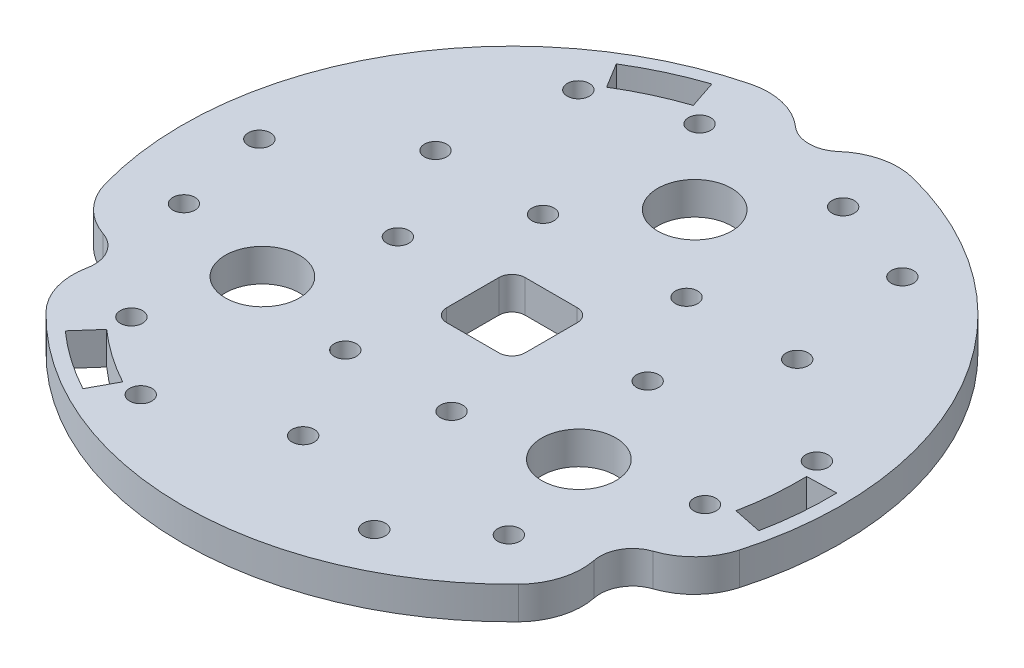
SolidWorks part; units mm, degrees
ref_plane "Front Plane" through (0, 0, 0) normal (0, 0, 1) x (1, 0, 0)
ref_plane "Top Plane" through (0, 0, 0) normal (0, 1, 0) x (1, 0, 0)
ref_plane "Right Plane" through (0, 0, 0) normal (1, 0, 0) x (0, 0, -1)
sketch "Sketch1" plane through (0, 0, 0) normal (0, 1, 0) x (1, 0, 0)
  line L0 (0, 0) -> (24.2487, -14) construction
  line L2 (0, 0) -> (0, 28) construction
  line L3 (0, 0) -> (-24.2487, -14) construction
  circle A0 centre (0, 0) radius 50.5
  circle A4 centre (0, 0) radius 28 construction
  circle A19 centre (0, 28) radius 5.675
  circle A20 centre (24.2487, -14) radius 5.675
  circle A21 centre (-24.2487, -14) radius 5.675
  point P13 (0, 0)
  point P38 (0, 0)
  dimension "D3" = 101
  dimension "D1" = 11.35
  dimension "D2" = 56
extrude "Boss-Extrude1" add sketch "Sketch1" along normal blind 5
sketch "Sketch4" plane through (0, 0, 0) normal (0, 1, 0) x (1, 0, 0)
  line L0 (0, 0) -> (27.7128, 16) construction
  line L1 (0, 0) -> (50.5, 0) construction
  line L2 (0, 0) -> (0, -32) construction
  line L3 (0, 0) -> (-27.7128, 16) construction
  circle A8 centre (27.7128, 16) radius 1.7
  circle A10 centre (0, 0) radius 50.5 construction
  circle A11 centre (0, -32) radius 1.7
  circle A12 centre (-27.7128, 16) radius 1.7
  point P12 (0, 0)
  dimension "D4" = 3.4
  dimension "D5" = 32
  dimension "D7" = 30
extrude "Cut-Extrude5" cut sketch "Sketch4" along normal through all
sketch "Sketch8" plane through (0, 5, 0) normal (0, 1, 0) x (1, 0, 0)
  line L0 (0, 0) -> (0, 28) construction
  line L3 (0, 28) -> (0, 50.5) construction
  circle A0 centre (0, 28) radius 5.675 construction
  circle A1 centre (0, 28) radius 5.675 construction
  circle A2 centre (11, 39.75) radius 1.7
  circle A4 centre (11, 15.75) radius 1.7
  circle A5 centre (-11, 39.75) radius 1.7
  circle A6 centre (-11, 15.75) radius 1.7
  circle A7 centre (0, 0) radius 50.5 construction
  dimension "D1" = 3.4
  dimension "D2" = 22
  dimension "D3" = 24
  dimension "D4" = 12.25
extrude "Cut-Extrude9" cut sketch "Sketch8" against normal through all
sketch "Sketch9" plane through (0, 0, 0) normal (0, -1, 0) x (1, 0, 0)
  line L0 (0, 0) -> (0, 45) construction
  line L1 (7.5, 45) -> (-7.5, 45) construction
  line L2 (-7.5, 45) -> (-17.8923, 39) construction
  line L3 (7.5, 45) -> (17.8923, 39) construction
  circle A0 centre (-17.8923, 39) radius 1.7
  circle A1 centre (17.8923, 39) radius 1.7
  dimension "D5" = 3.4
  dimension "D1" = 7.5
  dimension "D2" = 12
  dimension "D3" = 45
  dimension "D4" = 150
extrude "Cut-Extrude10" cut sketch "Sketch9" against normal through all
pattern_circular "CirPattern3" count 3 over 360 about axis through (0, 0, 0) along (0, 1, 0) of "Cut-Extrude9", "Cut-Extrude10"
sketch "Sketch10" plane through (0, 5, 0) normal (0, 1, 0) x (1, 0, 0)
  line L0 (0, 0) -> (-21.3422, 45.7685) construction
  line L1 (0, 0) -> (0, 50.5) construction
  line L2 (-13.9432, 41.7323) -> (-15.3692, 46.0004)
  line L3 (-23.0063, 37.5061) -> (-25.3592, 41.342)
  circle A0 centre (0, 0) radius 50.5 construction
  arc A2 (-25.3592, 41.342) -> (-15.3692, 46.0004) centre (0, 0) cw
  arc A3 (-23.0063, 37.5061) -> (-13.9432, 41.7323) centre (0, 0) cw
  point P5 (-18.5952, 39.8775)
  point P10 (-20.2671, 43.4629)
  point P13 (-18.7145, 40.1335)
  point P15 (-20.497, 43.9559)
  dimension "D2" = 2
  dimension "D3" = 4.5
  dimension "D5" = 10
  dimension "D1" = 25
  dimension "D4" = 4.5
extrude "Cut-Extrude11" cut sketch "Sketch10" against normal through all
pattern_circular "CirPattern4" count 3 over 360 about axis through (0, 0, 0) along (0, 1, 0) of "Cut-Extrude11"
sketch "Sketch11" plane through (0, 5, 0) normal (0, 1, 0) x (1, 0, 0)
  line L1 (-6, -6) -> (6, -6)
  line L2 (-6, -6) -> (-6, 6)
  line L3 (-6, 6) -> (6, 6)
  line L4 (6, -6) -> (6, 6)
  line L5 (-6, -6) -> (6, 6) construction
  line L6 (-6, 6) -> (6, -6) construction
  point P0 (0, 0)
  dimension "D1" = 12
  dimension "D2" = 12
extrude "Cut-Extrude12" cut sketch "Sketch11" against normal through all
fillet "Fillet1" radius 2 4 edges at (-6, 2.5, 6) (6, 2.5, 6) (6, 2.5, -6) (-6, 2.5, -6)
sketch "Sketch12" plane through (0, 5, 0) normal (0, 1, 0) x (1, 0, 0)
  line L0 (0, 0) -> (43.7343, -25.25) construction
  circle A0 centre (0, 0) radius 50.5
  circle A1 centre (24.2487, -14) radius 5.675 construction
  circle A2 centre (24.2487, -14) radius 5.675
  circle A3 centre (0, 0) radius 50.5 construction
  arc A4 (46.0169, -20.8014) -> (41.023, -29.4511) centre (43.7343, -25.25) ccw
  arc A5 (41.023, -29.4511) -> (46.0169, -20.8014) centre (43.7343, -25.25) ccw construction
  circle M47 centre (0, 0) radius 50.5
  dimension "D1" = 10
extrude "Cut-Extrude13" cut sketch "Sketch12" against normal through all contours A4 M47
fillet "Fillet2" radius 10 2 edges at (41.023, 2.5, 29.4511) (46.0169, 2.5, 20.8014)
pattern_circular "CirPattern5" count 3 over 360 about axis through (0, 0, 0) along (0, 1, 0) of "Cut-Extrude13", "Fillet2"
